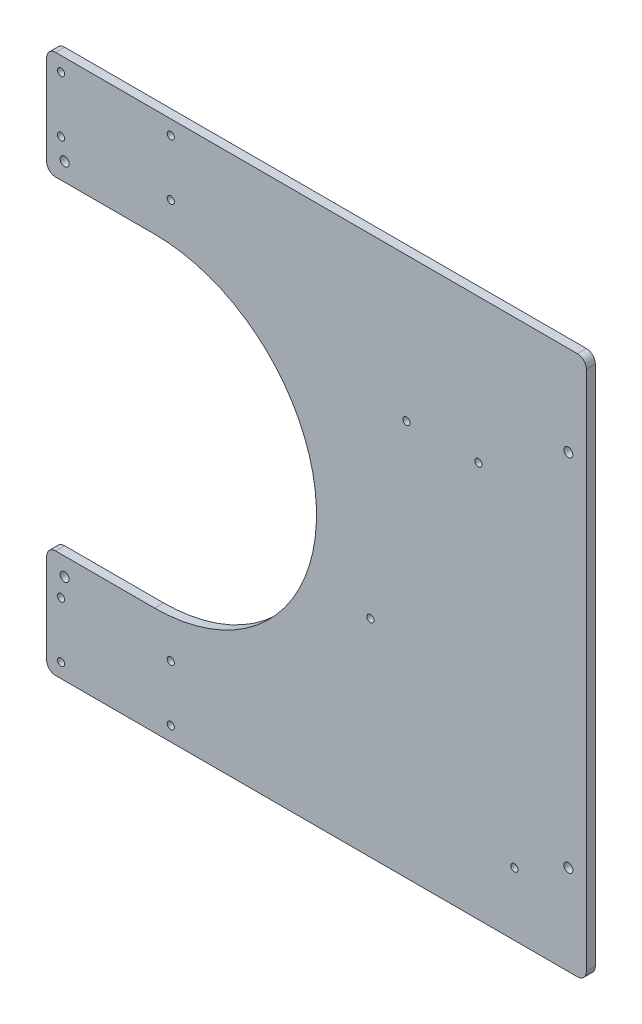
SolidWorks part; units mm, degrees
ref_plane "前视基准面" through (0, 0, 0) normal (0, 0, 1) x (1, 0, 0)
ref_plane "上视基准面" through (0, 0, 0) normal (0, 1, 0) x (1, 0, 0)
ref_plane "右视基准面" through (0, 0, 0) normal (1, 0, 0) x (0, 0, -1)
other "Configuration Table"
sketch "草图1" plane through (0, 0, 0) normal (0, 0, 1) x (1, 0, 0)
  line L0 (60, 150) -> (300, 150) construction
  line L1 (5, 0) -> (295, 0)
  line L2 (0, 5) -> (0, 55)
  line L3 (5, 300) -> (295, 300)
  line L4 (300, 5) -> (300, 295)
  line L5 (150, 300) -> (150, 0) construction
  line L6 (5, 240) -> (60, 240)
  line L9 (5, 60) -> (60, 60)
  line L11 (0, 245) -> (0, 295)
  line L12 (60, 240) -> (60, 60) construction
  line L13 (0, 300) -> (80, 300) construction
  line L14 (0, 300) -> (0, 260) construction
  line L15 (0, 260) -> (80, 260) construction
  line L16 (80, 300) -> (80, 260) construction
  line L17 (170, 220) -> (270, 220) construction
  line L18 (8, 292) -> (69, 292) construction
  line L19 (8, 292) -> (8, 261) construction
  line L20 (8, 261) -> (69, 261) construction
  line L21 (69, 292) -> (69, 261) construction
  line L22 (170, 125) -> (270, 125) construction
  line L23 (170, 125) -> (170, 25) construction
  line L24 (170, 25) -> (270, 25) construction
  line L25 (270, 125) -> (270, 25) construction
  line L26 (170, 75) -> (270, 75) construction
  line L27 (220, 125) -> (220, 25) construction
  arc A0 (60, 240) -> (60, 60) centre (60, 150) cw
  circle A1 centre (10, 250) radius 2.5
  circle A2 centre (290, 250) radius 2.5
  circle A3 centre (10, 50) radius 2.5
  circle A4 centre (290, 50) radius 2.5
  arc A5 (0, 55) -> (5, 60) centre (5, 55) cw
  arc A6 (5, 0) -> (0, 5) centre (5, 5) cw
  arc A7 (295, 0) -> (300, 5) centre (295, 5) ccw
  arc A8 (295, 300) -> (300, 295) centre (295, 295) cw
  arc A9 (5, 240) -> (0, 245) centre (5, 245) cw
  arc A10 (0, 295) -> (5, 300) centre (5, 295) cw
  circle A11 centre (8, 292) radius 2
  circle A12 centre (69, 292) radius 2
  circle A13 centre (69, 261) radius 2
  circle A14 centre (8, 261) radius 2
  circle A15 centre (8, 39) radius 2
  circle A16 centre (69, 39) radius 2
  circle A17 centre (69, 8) radius 2
  circle A18 centre (8, 8) radius 2
  circle A19 centre (220, 220) radius 50 construction
  circle A20 centre (200, 220) radius 2
  circle A21 centre (240, 220) radius 2
  circle A22 centre (180, 115) radius 2
  circle A23 centre (260, 35) radius 2
  point P28 (0, 60)
  point P31 (0, 0)
  point P34 (300, 0)
  point P37 (300, 300)
  point P40 (0, 240)
  point P80 (174.0363, 114.7158)
  point P81 (262.7785, 25)
  dimension "D7" = 5
  dimension "D10" = 5
  dimension "D14" = 4
  dimension "D15" = 4
  dimension "D16" = 4
  dimension "D17" = 4
  dimension "D19" = 100
  dimension "D22" = 4
  dimension "D24" = 4
  dimension "D30" = 4
  dimension "D31" = 4
  dimension "D1" = 300
  dimension "D2" = 300
  dimension "D3" = 60
  dimension "D4" = 90
  dimension "D5" = 40
  dimension "D6" = 80
  dimension "D8" = 10
  dimension "D9" = 10
  dimension "D11" = 31
  dimension "D12" = 61
  dimension "D13" = 8
  dimension "D18" = 8
  dimension "D20" = 100
  dimension "D21" = 100
  dimension "D23" = 20
  dimension "D25" = 20
  dimension "D26" = 80
  dimension "D27" = 80
  dimension "D28" = 30
  dimension "D29" = 25
  dimension "D32" = 10
  dimension "D33" = 10
  dimension "D34" = 10
  dimension "D35" = 10
extrude "凸台-拉伸1" add sketch "草图1" along normal blind 5
